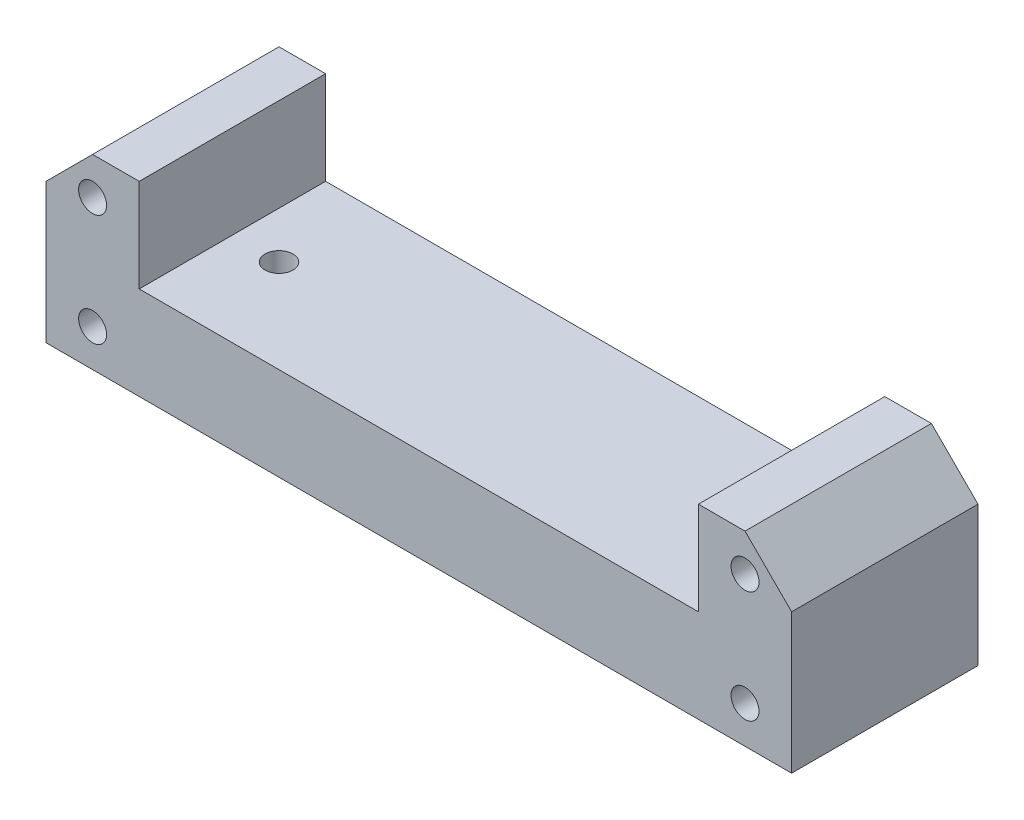
SolidWorks part; units mm, degrees
material "POM 乙缩醛共聚物"
ref_plane "前视基准面" through (0, 0, 0) normal (0, 0, 1) x (1, 0, 0)
ref_plane "上视基准面" through (0, 0, 0) normal (0, 1, 0) x (1, 0, 0)
ref_plane "右视基准面" through (0, 0, 0) normal (1, 0, 0) x (0, 0, -1)
sketch "草图1" plane through (0, 0, 0) normal (0, 1, 0) x (1, 0, 0)
  line L1 (-40, -10) -> (40, -10)
  line L2 (-40, -10) -> (-40, 10)
  line L3 (-40, 10) -> (40, 10)
  line L4 (40, -10) -> (40, 10)
  line L5 (-40, -10) -> (40, 10) construction
  line L6 (-40, 10) -> (40, -10) construction
  point P0 (0, 0)
  dimension "D1" = 20
  dimension "D2" = 80
extrude "凸台-拉伸1" add sketch "草图1" along normal blind 20
sketch "草图2" plane through (0, 20, 0) normal (0, 1, 0) x (1, 0, 0)
  line L0 (40, 10) -> (-40, 10) construction
  line L1 (-30, -10) -> (30, -10)
  line L2 (-30, -10) -> (-30, 10)
  line L3 (-30, 10) -> (30, 10)
  line L4 (30, -10) -> (30, 10)
  line L5 (-30, -10) -> (30, 10) construction
  line L6 (-30, 10) -> (30, -10) construction
  point P0 (0, 0)
  point P6 (20.8198, 10)
  dimension "D1" = 60
extrude "切除-拉伸1" cut sketch "草图2" against normal blind 10
sketch "草图3" plane through (0, 10, 0) normal (0, 1, 0) x (1, 0, 0)
  line L0 (-30, 0) -> (30, 0) construction
  line L1 (-30, 10) -> (-30, -10) construction
  line L2 (30, -10) -> (30, 10) construction
  line L3 (0, 10) -> (0, -10) construction
  line L4 (30, 10) -> (-30, 10) construction
  line L5 (-30, -10) -> (30, -10) construction
  circle A0 centre (-25, 0) radius 1.5
  circle A1 centre (25, 0) radius 1.5
  dimension "D1" = 3
  dimension "D2" = 25
extrude "切除-拉伸2" cut sketch "草图3" against normal through all
chamfer "倒角1" distance 5 angle 45 2 edges at (-40, 20, 0) (40, 20, 0)
sketch "草图4" plane through (0, 0, 10) normal (0, 0, 1) x (1, 0, 0)
  line L0 (0, 0) -> (0, 10) construction
  line L1 (-30, 10) -> (30, 10) construction
  line L2 (-35, 0) -> (-35, 20) construction
  line L3 (-40, 0) -> (40, 0) construction
  line L4 (-35, 20) -> (-30, 20) construction
  circle A0 centre (-35, 16) radius 1.5
  circle A1 centre (-35, 4) radius 1.5
  circle A2 centre (35, 4) radius 1.5
  circle A3 centre (35, 16) radius 1.5
  dimension "D2" = 3
  dimension "D3" = 6
  dimension "D1" = 35
extrude "切除-拉伸3" cut sketch "草图4" against normal through all
